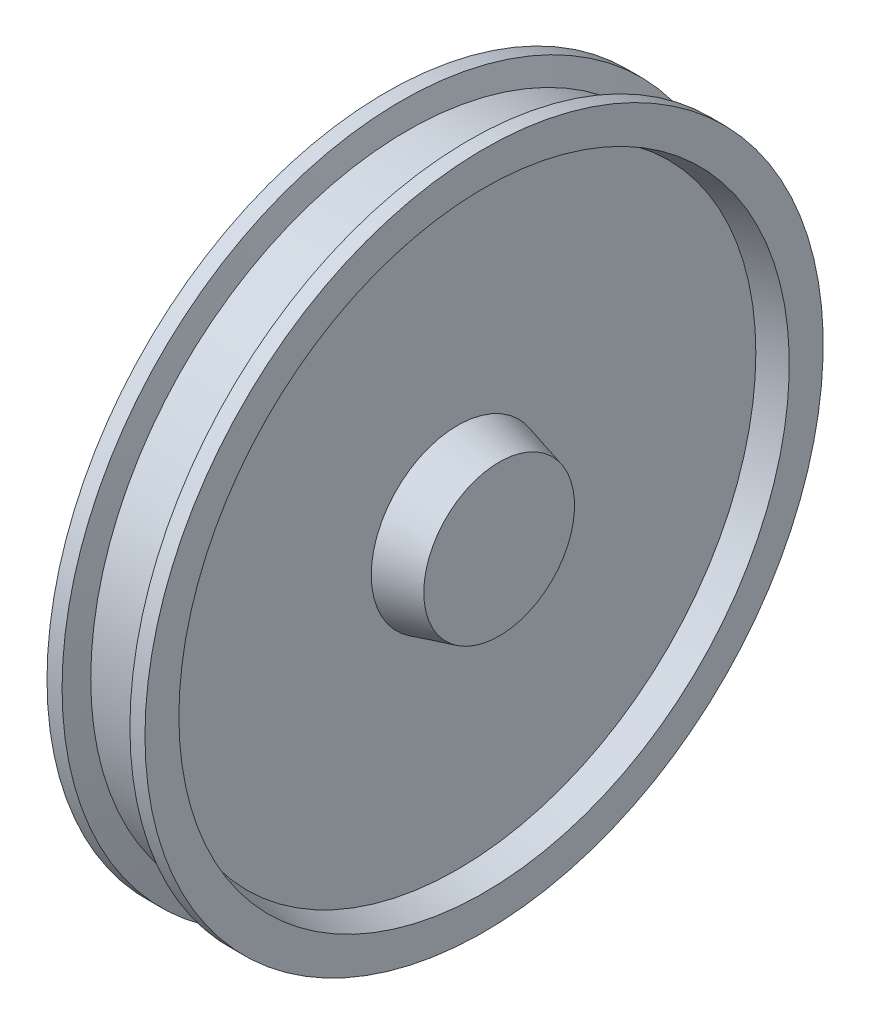
SolidWorks part; units mm, degrees
material "Alliage 1060"
ref_plane "Plan de face" through (0, 0, 0) normal (0, 0, 1) x (1, 0, 0)
ref_plane "Plan de dessus" through (0, 0, 0) normal (0, 1, 0) x (1, 0, 0)
ref_plane "Plan de droite" through (0, 0, 0) normal (1, 0, 0) x (0, 0, -1)
sketch "Esquisse2" plane through (0, 0, 0) normal (0, 0, 1) x (1, 0, 0)
  line L0 (-253.8578, 0) -> (292.7566, 0) construction
  line L1 (0, 0) -> (0, 1083.7927) construction
  line L2 (-85, 0) -> (-85, 100)
  line L3 (-85, 100) -> (-30, 114.7372)
  line L4 (-30, 114.7372) -> (-30, 395.6218)
  line L5 (-30, 395.6218) -> (-65, 405)
  line L6 (-65, 405) -> (-65, 450)
  line L7 (-65, 450) -> (-45, 450)
  line L8 (-45, 450) -> (-36.9615, 420)
  line L9 (-36.9615, 420) -> (36.9615, 420)
  line L10 (-85, 100) -> (7.799, 100) construction
  line L11 (-45, 450) -> (-45, 414.1636) construction
  line L12 (-65, 405) -> (-11.8684, 405) construction
  line L13 (30, 114.7372) -> (30, 395.6218)
  line L14 (65, 405) -> (11.8684, 405) construction
  line L15 (45, 450) -> (45, 414.1636) construction
  line L16 (85, 100) -> (-7.799, 100) construction
  line L17 (253.8578, 0) -> (-292.7566, 0) construction
  line L18 (45, 450) -> (36.9615, 420)
  line L19 (65, 450) -> (45, 450)
  line L20 (65, 405) -> (65, 450)
  line L21 (30, 395.6218) -> (65, 405)
  line L22 (85, 100) -> (30, 114.7372)
  line L23 (85, 0) -> (85, 100)
  line L24 (-85, 0) -> (85, 0)
  point P28 (0, 420)
  dimension "D1" = 900
  dimension "D2" = 15
  dimension "D3" = 20
  dimension "D4" = 30
  dimension "D5" = 15
  dimension "D6" = 15
  dimension "D7" = 130
  dimension "D8" = 170
  dimension "D9" = 60
  dimension "D10" = 170
  dimension "D11" = 100
  dimension "D12" = 45
revolve "Révolution1" add sketch "Esquisse2" angle 360 about L24
equation "\"A\"= 130"
equation "\"B\"= 900"
equation "\"D1@Esquisse2\"=\"B\""
equation "\"D7@Esquisse2\"=\"A\""
equation "\"D8@Esquisse2\"=\"A\" +40"
